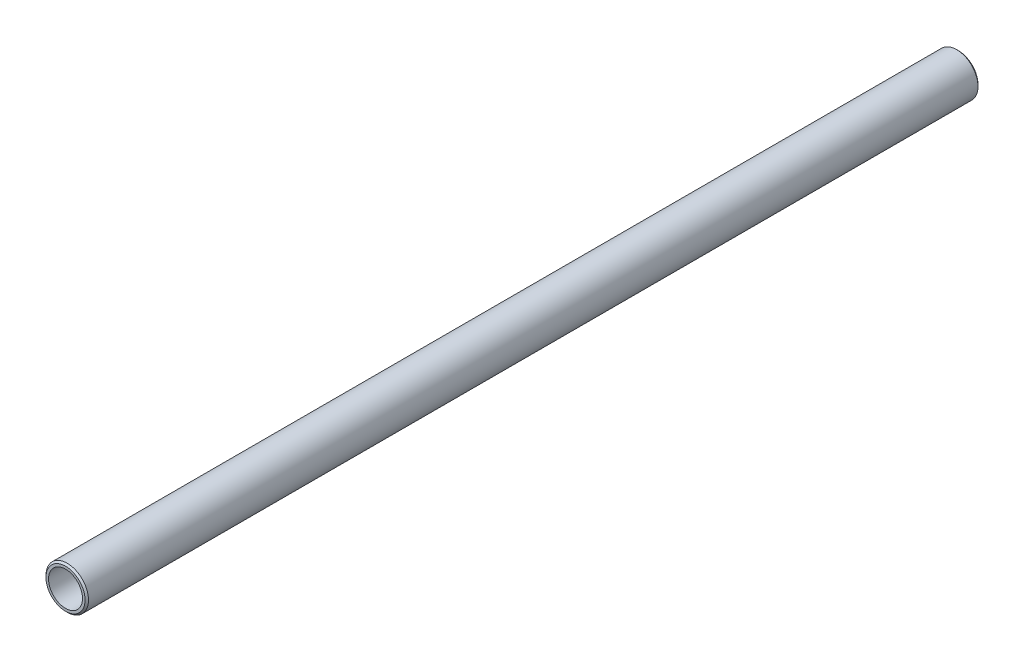
SolidWorks part; units mm, degrees
material "1060 Alloy"
ref_plane "Front Plane" through (0, 0, 0) normal (0, 0, 1) x (1, 0, 0)
ref_plane "Top Plane" through (0, 0, 0) normal (0, 1, 0) x (1, 0, 0)
ref_plane "Right Plane" through (0, 0, 0) normal (1, 0, 0) x (0, 0, -1)
sketch "Sketch1" plane through (0, 0, 0) normal (0, 0, 1) x (1, 0, 0)
  circle A0 centre (0, 0) radius 5
  circle A1 centre (0, 0) radius 4
  dimension "D1" = 10
  dimension "D2" = 8
extrude "body" add sketch "Sketch1" along normal blind 210
chamfer "end_chamfers" distance 0.4 angle 45 2 edges at (5, 0, 0) (5, 0, 210)
